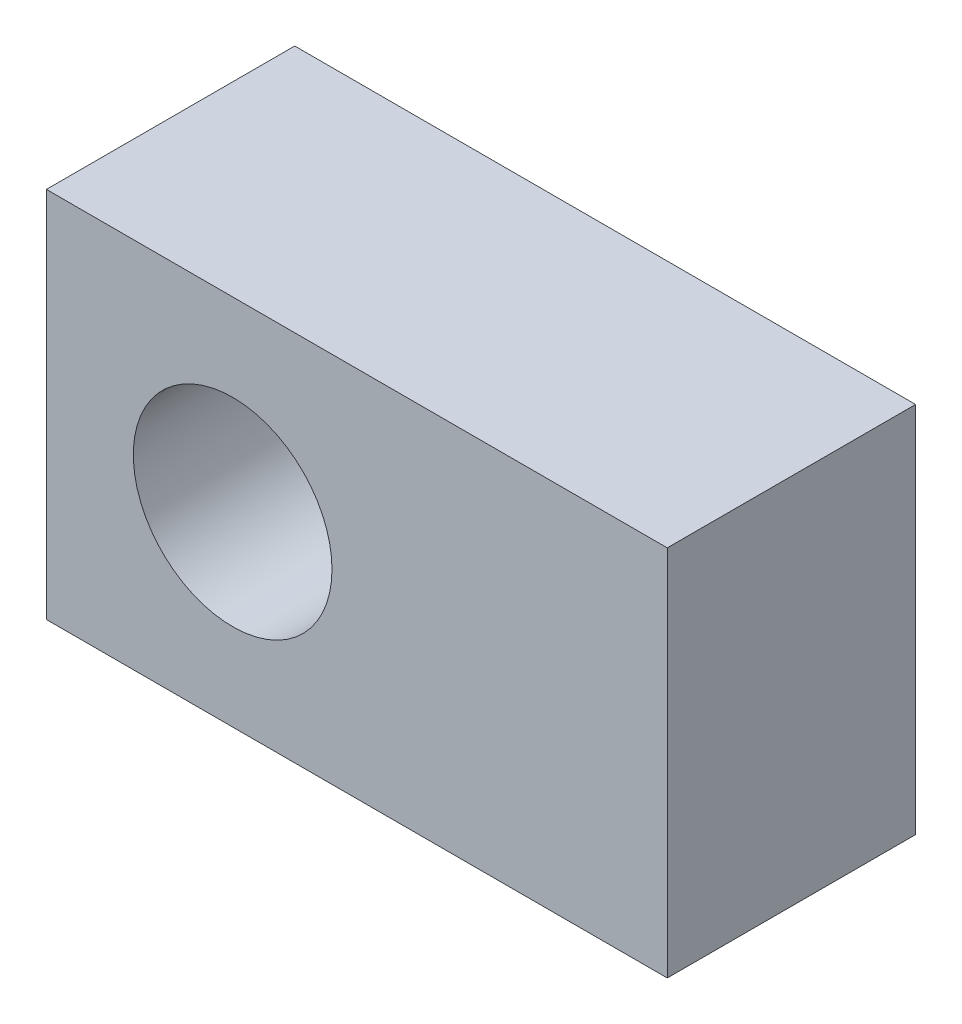
SolidWorks part; units mm, degrees
ref_plane "Front Plane" through (0, 0, 0) normal (0, 0, 1) x (1, 0, 0)
ref_plane "Top Plane" through (0, 0, 0) normal (0, 1, 0) x (1, 0, 0)
ref_plane "Right Plane" through (0, 0, 0) normal (1, 0, 0) x (0, 0, -1)
sketch "Sketch2" plane through (0, 0, 0) normal (0, 0, 1) x (1, 0, 0)
  line L1 (0, 0) -> (25, 0)
  line L2 (0, 0) -> (0, 15)
  line L3 (0, 15) -> (25, 15)
  line L4 (25, 0) -> (25, 15)
  circle A0 centre (7.5, 7.5) radius 4
  point P7 (5.5994, 7.5)
  point P9 (0, 6.4549)
  dimension "D3" = 8
  dimension "D1" = 25
  dimension "D2" = 15
  dimension "D4" = 7.5
  dimension "D5" = 7.5
extrude "Boss-Extrude1" add sketch "Sketch2" along normal blind 10
